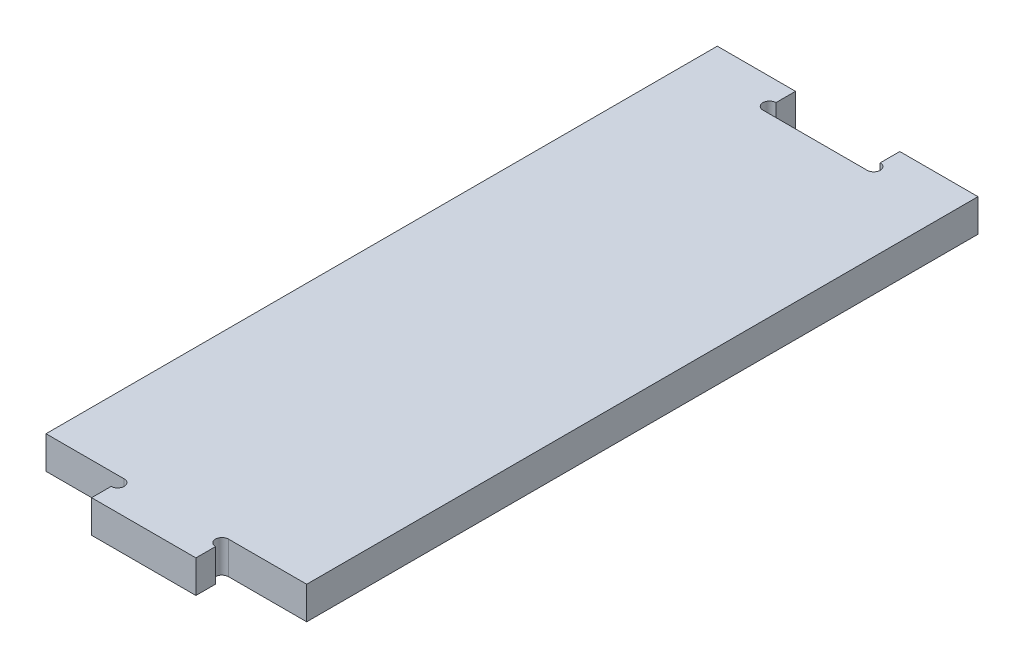
SolidWorks part; units mm, degrees
material "유리"
ref_plane "정면" through (0, 0, 0) normal (0, 0, 1) x (1, 0, 0)
ref_plane "윗면" through (0, 0, 0) normal (0, 1, 0) x (1, 0, 0)
ref_plane "우측면" through (0, 0, 0) normal (1, 0, 0) x (0, 0, -1)
sketch "스케치1" plane through (0, 0, 0) normal (0, 1, 0) x (1, 0, 0)
  line L1 (0, 0) -> (40, 0)
  line L2 (0, 0) -> (0, 103)
  line L3 (0, 103) -> (40, 103)
  line L4 (40, 0) -> (40, 103)
  dimension "D1" = 103
  dimension "D2" = 40
extrude "보스-돌출1" add sketch "스케치1" along normal blind 5
sketch "스케치2" plane through (0, 5, 0) normal (0, 1, 0) x (1, 0, 0)
  line L0 (40, 103) -> (0, 103) construction
  line L1 (12, 103) -> (28, 103)
  line L2 (12, 103) -> (12, 98)
  line L3 (12, 98) -> (28, 98)
  line L4 (28, 103) -> (28, 98)
  line L5 (40, 0) -> (40, 103) construction
  line L6 (0, 103) -> (0, 0) construction
  dimension "D1" = 12
  dimension "D2" = 12
  dimension "D3" = 5
sketch "스케치3" plane through (0, 5, 0) normal (0, 1, 0) x (1, 0, 0)
  line L0 (0, 0) -> (40, 0) construction
  line L1 (12, 0) -> (28, 0)
  line L2 (12, 0) -> (12, -5)
  line L3 (12, -5) -> (28, -5)
  line L4 (28, 0) -> (28, -5)
  line L5 (40, 0) -> (40, 103) construction
  line L6 (0, 103) -> (0, 0) construction
  dimension "D1" = 12
  dimension "D2" = 12
  dimension "D3" = 5
extrude "컷-돌출2" cut sketch "스케치2" against normal blind 5
extrude "보스-돌출3" add sketch "스케치3" against normal blind 5
sketch "스케치4" plane through (0, 5, 0) normal (0, 1, 0) x (1, 0, 0)
  line L0 (28, -5) -> (28, 0) construction
  line L1 (12, 0) -> (12, -5) construction
  line L2 (12, 103) -> (12, 98) construction
  line L3 (28, 98) -> (28, 103) construction
  circle A0 centre (28, -1) radius 1
  circle A1 centre (12, -1) radius 1
  circle A2 centre (12, 99) radius 1
  circle A3 centre (28, 99) radius 1
  dimension "D1" = 2
extrude "컷-돌출3" cut sketch "스케치4" against normal blind 10
